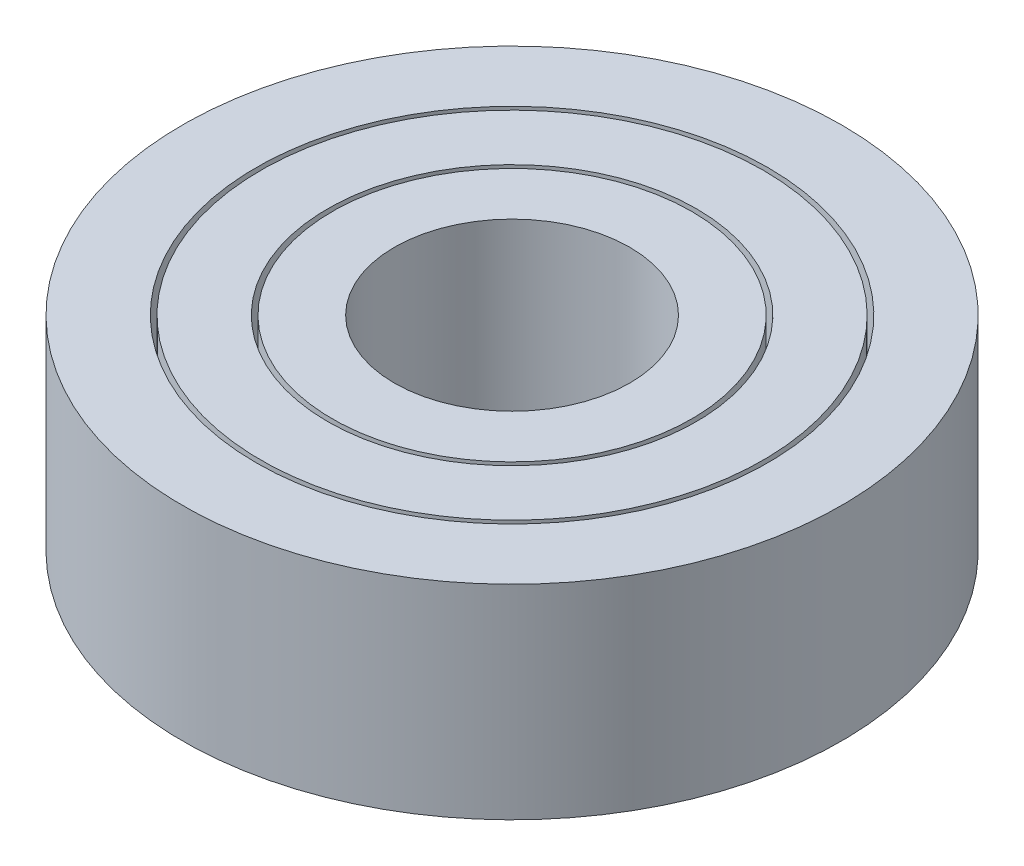
SolidWorks part; units mm, degrees
ref_plane "Front Plane" through (0, 0, 0) normal (0, 0, 1) x (1, 0, 0)
ref_plane "Top Plane" through (0, 0, 0) normal (0, 1, 0) x (1, 0, 0)
ref_plane "Right Plane" through (0, 0, 0) normal (1, 0, 0) x (0, 0, -1)
sketch "Sketch1" plane through (0, 0, 0) normal (0, 1, 0) x (1, 0, 0)
  circle A0 centre (0, 0) radius 7.5
  circle A1 centre (0, 0) radius 11.75
  circle A2 centre (0, 0) radius 16
  circle A3 centre (0, 0) radius 21
  circle A4 centre (0, 0) radius 16.3
  dimension "D1" = 42
  dimension "D2" = 15
  dimension "D3" = 32
  dimension "D4" = 23.5
  dimension "D5" = 0.3
extrude "Boss-Extrude1" add sketch "Sketch1" along normal blind 13 contours A3 A4
sketch "Sketch2" plane through (0, 0, 0) normal (0, 1, 0) x (1, 0, 0)
  circle A0 centre (0, 0) radius 11.75 construction
  circle A1 centre (0, 0) radius 16 construction
  circle A2 centre (0, 0) radius 11.75
  circle A3 centre (0, 0) radius 16
extrude "Boss-Extrude2" add sketch "Sketch2" along normal blind 13 separate body
sketch "Sketch3" plane through (0, 0, 0) normal (0, 1, 0) x (1, 0, 0)
  circle A0 centre (0, 0) radius 7.5 construction
  circle A1 centre (0, 0) radius 11.75 construction
  circle A2 centre (0, 0) radius 7.5
  circle A3 centre (0, 0) radius 11.75
  circle A4 centre (0, 0) radius 11.45
  dimension "D1" = 0.3
extrude "Boss-Extrude4" add sketch "Sketch3" along normal blind 13 separate body contours A4 A2
